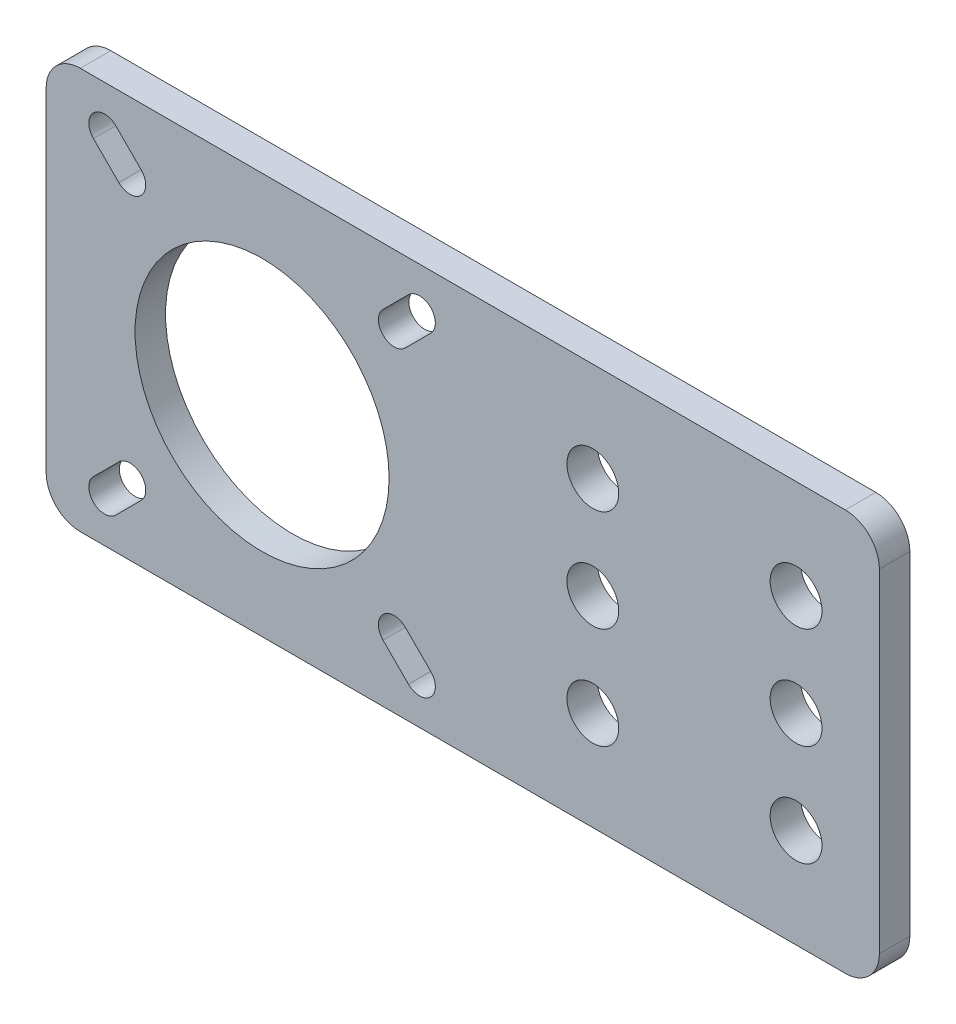
SolidWorks part; units mm, degrees
material "Plain Carbon Steel"
ref_plane "Plan de face" through (0, 0, 0) normal (0, 0, 1) x (1, 0, 0)
ref_plane "Plan de dessus" through (0, 0, 0) normal (0, 1, 0) x (1, 0, 0)
ref_plane "Plan de droite" through (0, 0, 0) normal (1, 0, 0) x (0, 0, -1)
sketch "Esquisse1" plane through (0, 0, 0) normal (0, 0, 1) x (1, 0, 0)
  line L0 (-4.25, 15.5) -> (-6.75, 13) construction
  line L1 (-37.64, -19.75) -> (37.64, -19.75)
  line L2 (-41, -16.39) -> (-41, 16.39)
  line L3 (-37.64, 19.75) -> (37.64, 19.75)
  line L4 (41, -16.39) -> (41, 16.39)
  line L5 (-41, -19.75) -> (41, 19.75) construction
  line L6 (-41, 19.75) -> (41, -19.75) construction
  line L7 (-3.154, 14.404) -> (-5.654, 11.904)
  line L8 (-5.346, 16.596) -> (-7.846, 14.096)
  line L9 (-4.25, -15.5) -> (-6.75, -13) construction
  line L10 (-5.346, -16.596) -> (-7.846, -14.096)
  line L11 (-3.154, -14.404) -> (-5.654, -11.904)
  line L12 (-35.25, -15.5) -> (-32.75, -13) construction
  line L13 (-36.346, -14.404) -> (-33.846, -11.904)
  line L14 (-34.154, -16.596) -> (-31.654, -14.096)
  line L15 (0, 0) -> (12.8, 0) construction
  line L16 (12.8, 0) -> (12.8, 10) construction
  line L19 (-35.25, 15.5) -> (-32.75, 13) construction
  line L20 (-34.154, 16.596) -> (-31.654, 14.096)
  line L21 (-36.346, 14.404) -> (-33.846, 11.904)
  arc A0 (-37.64, -19.75) -> (-41, -16.39) centre (-37.64, -16.39) cw
  arc A1 (37.64, -19.75) -> (41, -16.39) centre (37.64, -16.39) ccw
  arc A2 (37.64, 19.75) -> (41, 16.39) centre (37.64, 16.39) cw
  arc A3 (-41, 16.39) -> (-37.64, 19.75) centre (-37.64, 16.39) cw
  circle A4 centre (-19.75, 0) radius 12.5
  arc A5 (-34.154, 16.596) -> (-36.346, 14.404) centre (-35.25, 15.5) ccw
  arc A6 (-33.846, 11.904) -> (-31.654, 14.096) centre (-32.75, 13) ccw
  arc A7 (-3.154, 14.404) -> (-5.346, 16.596) centre (-4.25, 15.5) ccw
  arc A8 (-7.846, 14.096) -> (-5.654, 11.904) centre (-6.75, 13) ccw
  arc A9 (-5.346, -16.596) -> (-3.154, -14.404) centre (-4.25, -15.5) ccw
  arc A10 (-5.654, -11.904) -> (-7.846, -14.096) centre (-6.75, -13) ccw
  arc A11 (-36.346, -14.404) -> (-34.154, -16.596) centre (-35.25, -15.5) ccw
  arc A12 (-31.654, -14.096) -> (-33.846, -11.904) centre (-32.75, -13) ccw
  circle A13 centre (12.8, 10) radius 2.55
  circle A14 centre (32.8, 10) radius 2.55
  circle A15 centre (12.8, 0) radius 2.55
  circle A16 centre (32.8, 0) radius 2.55
  circle A17 centre (12.8, -10) radius 2.55
  circle A18 centre (32.8, -10) radius 2.55
  point P0 (0, 0)
  point P25 (-5.5, 14.25)
  point P27 (-34, 14.25)
  point P38 (-5.5, -14.25)
  point P45 (-34, -14.25)
  dimension "D3" = 3.36
  dimension "D4" = 25
  dimension "D13" = 5.1
  dimension "D1" = 39.5
  dimension "D2" = 82
  dimension "D5" = 45
  dimension "D6" = 5.75
  dimension "D7" = 6.75
  dimension "D8" = 3.1
  dimension "D9" = 8.25
  dimension "D11" = 10
  dimension "D12" = 53.8
  dimension "D16" = 20
  dimension "D14" = 2
  dimension "D15" = 3
  dimension "D10" = 4
extrude "Boss.-Extru.1" add sketch "Esquisse1" along normal mid plane 3
